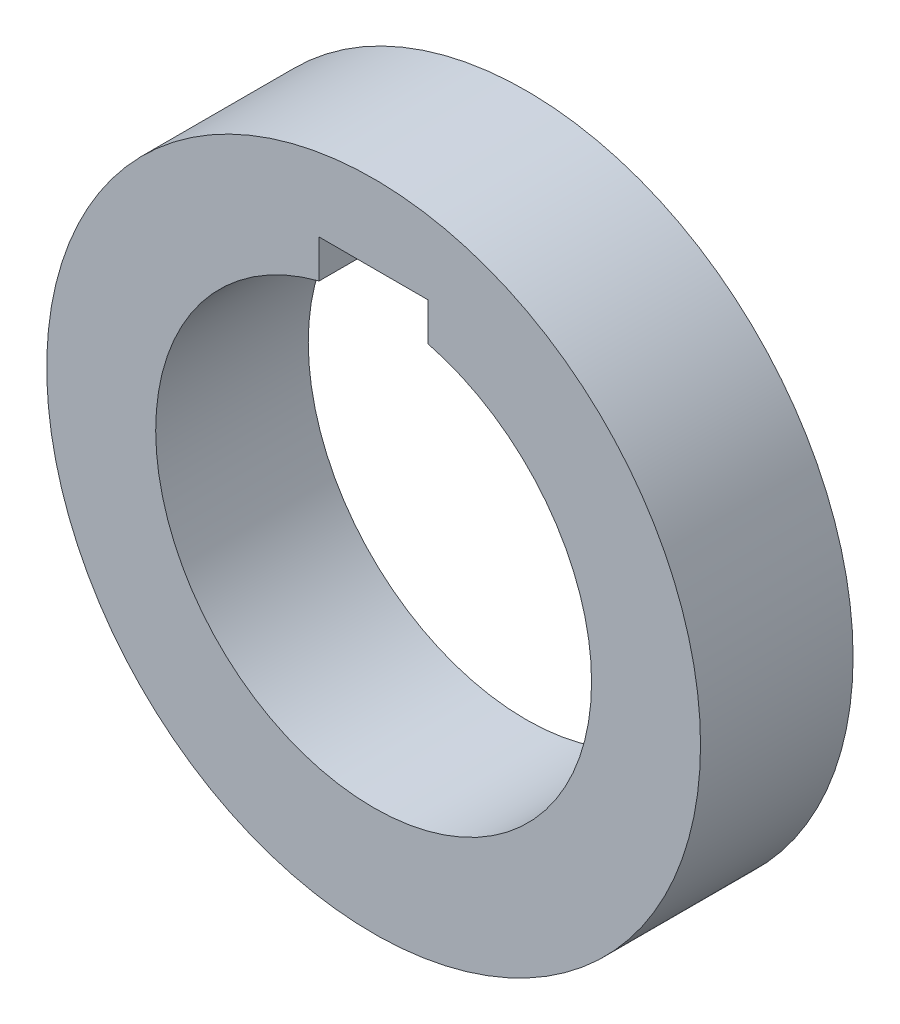
SolidWorks part; units mm, degrees
ref_plane "Front Plane" through (0, 0, 0) normal (0, 0, 1) x (1, 0, 0)
ref_plane "Top Plane" through (0, 0, 0) normal (0, 1, 0) x (1, 0, 0)
ref_plane "Right Plane" through (0, 0, 0) normal (1, 0, 0) x (0, 0, -1)
sketch "Sketch1" plane through (0, 0, 0) normal (0, 0, 1) x (1, 0, 0)
  line L0 (-2.5, 9.6825) -> (-2.5, 11.43)
  line L1 (-2.5, 11.43) -> (2.5, 11.43)
  line L2 (2.5, 11.43) -> (2.5, 9.6825)
  circle A0 centre (0, 0) radius 15
  arc A1 (-2.5, 9.6825) -> (2.5, 9.6825) centre (0, 0) ccw
  point P4 (0, 11.43)
  dimension "D1" = 20
  dimension "D2" = 30
  dimension "D3" = 11.43
  dimension "D4" = 5
extrude "Boss-Extrude1" add sketch "Sketch1" along normal blind 7 contours A1 L2 L1 L0
